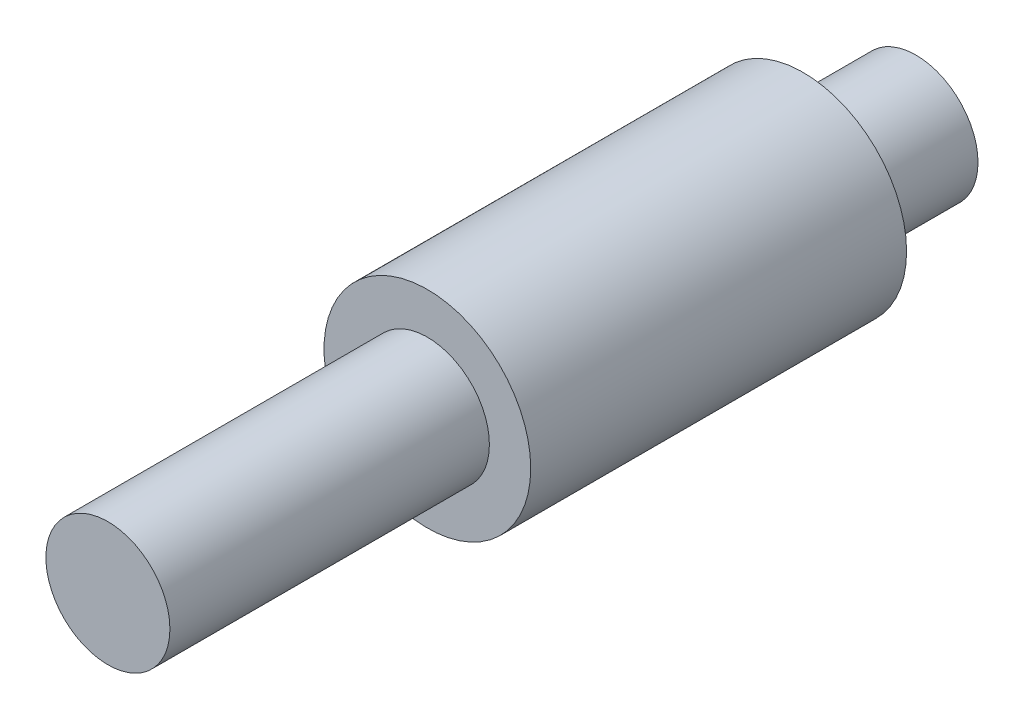
SolidWorks part; units mm, degrees
ref_plane "前视基准面" through (0, 0, 0) normal (0, 0, 1) x (1, 0, 0)
ref_plane "上视基准面" through (0, 0, 0) normal (0, 1, 0) x (1, 0, 0)
ref_plane "右视基准面" through (0, 0, 0) normal (1, 0, 0) x (0, 0, -1)
sketch "草图1" plane through (0, 0, 0) normal (0, 1, 0) x (1, 0, 0)
  line L0 (3.3, 0) -> (0, 0)
  line L1 (0, 0) -> (0, -43)
  line L2 (0, -43) -> (3.3, -43)
  line L3 (3.3, -43) -> (3.3, -26)
  line L4 (3.3, -26) -> (5.5, -26)
  line L5 (5.5, -26) -> (5.5, -6)
  line L6 (5.5, -6) -> (3.3, -6)
  line L7 (3.3, -6) -> (3.3, 0)
  line L8 (0, 0) -> (0, -43) construction
revolve "旋转1" add sketch "草图1" angle 360 about L8
